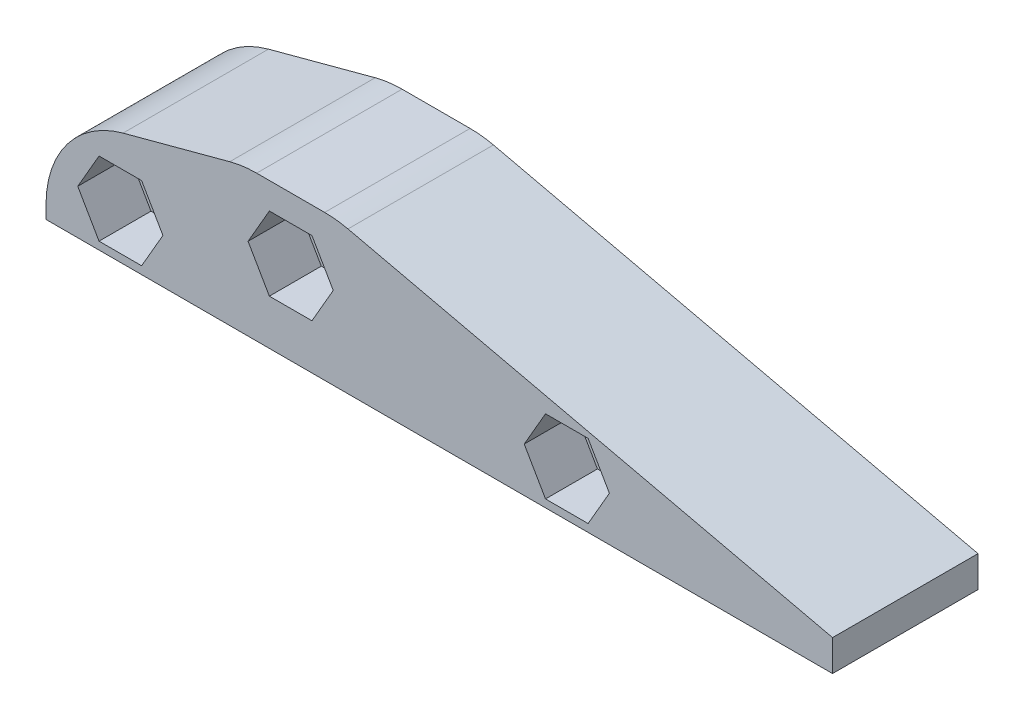
SolidWorks part; units mm, degrees
material "ABS"
ref_plane "Front Plane" through (0, 0, 0) normal (0, 0, 1) x (1, 0, 0)
ref_plane "Top Plane" through (0, 0, 0) normal (0, 1, 0) x (1, 0, 0)
ref_plane "Right Plane" through (0, 0, 0) normal (1, 0, 0) x (0, 0, -1)
sketch "Sketch1" plane through (0, 0, 0) normal (0, 0, 1) x (1, 0, 0)
  line L0 (0, 0) -> (0, 8.92)
  line L1 (0, 8.92) -> (18.9588, 14)
  line L2 (18.9588, 14) -> (27.9588, 14)
  line L3 (27.9588, 14) -> (75.7082, 3)
  line L4 (75.7082, 3) -> (75.7082, 0)
  line L5 (75.7082, 0) -> (0, 0)
  line L6 (0, 0) -> (0, 23.7543) construction
  dimension "D1" = 8.92
  dimension "D2" = 75
  dimension "D3" = 9
  dimension "D4" = 14
  dimension "D5" = 49
  dimension "D6" = 3
extrude "Boss-Extrude1" add sketch "Sketch1" along normal blind 14
fillet "Fillet1" radius 10 1 edges at (0, 8.92, 7)
fillet "Fillet2" radius 10 2 edges at (27.9588, 14, 7) (18.9588, 14, 7)
sketch "Sketch2" plane through (0, 0, 14) normal (0, 0, 1) x (1, 0, 0)
  point P0 (7.155, 4.2936)
  point P1 (23.5486, 7.9069)
  point P2 (50.1296, 4.2936)
sketch "Sketch3" plane through (0, 0, 14) normal (0, 0, 1) x (1, 0, 0)
  line L0 (0, 0) -> (75.7082, 0) construction
  line L1 (9.2046, 0.7436) -> (11.2542, 4.2936)
  line L2 (11.2542, 4.2936) -> (9.2046, 7.8436)
  line L3 (9.2046, 7.8436) -> (5.1054, 7.8436)
  line L4 (5.1054, 7.8436) -> (3.0558, 4.2936)
  line L5 (3.0558, 4.2936) -> (5.1054, 0.7436)
  line L6 (5.1054, 0.7436) -> (9.2046, 0.7436)
  line L7 (25.5982, 4.3569) -> (27.6478, 7.9069)
  line L8 (27.6478, 7.9069) -> (25.5982, 11.4569)
  line L9 (25.5982, 11.4569) -> (21.499, 11.4569)
  line L10 (21.499, 11.4569) -> (19.4494, 7.9069)
  line L11 (19.4494, 7.9069) -> (21.499, 4.3569)
  line L12 (21.499, 4.3569) -> (25.5982, 4.3569)
  line L13 (52.1792, 0.7436) -> (54.2288, 4.2936)
  line L14 (54.2288, 4.2936) -> (52.1792, 7.8436)
  line L15 (52.1792, 7.8436) -> (48.0801, 7.8436)
  line L16 (48.0801, 7.8436) -> (46.0305, 4.2936)
  line L17 (46.0305, 4.2936) -> (48.0801, 0.7436)
  line L18 (48.0801, 0.7436) -> (52.1792, 0.7436)
  circle A0 centre (7.155, 4.2936) radius 3.55 construction
  circle A1 centre (23.5486, 7.9069) radius 3.55 construction
  circle A2 centre (50.1296, 4.2936) radius 3.55 construction
  dimension "D1" = 7.1
  dimension "D2" = 7.1
  dimension "D3" = 7.1
extrude "Cut-Extrude1" cut sketch "Sketch3" against normal blind 5
sketch "Sketch4" plane through (0, 0, 9) normal (0, 0, 1) x (1, 0, 0)
  circle A0 centre (7.155, 4.2936) radius 2.05
  circle A1 centre (23.5486, 7.9069) radius 2.05
  circle A2 centre (50.1296, 4.2936) radius 2.05
  dimension "D1" = 4.1
extrude "Cut-Extrude2" cut sketch "Sketch4" against normal through all
